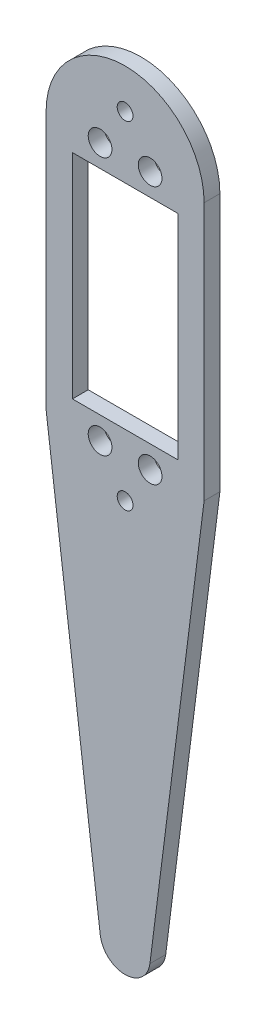
SolidWorks part; units mm, degrees
ref_plane "Front Plane" through (0, 0, 0) normal (0, 0, 1) x (1, 0, 0)
ref_plane "Top Plane" through (0, 0, 0) normal (0, 1, 0) x (1, 0, 0)
ref_plane "Right Plane" through (0, 0, 0) normal (1, 0, 0) x (0, 0, -1)
sketch "Sketch1" plane through (0, 0, 0) normal (0, 0, 1) x (1, 0, 0)
  line L0 (-5, -1011.6385) -> (-5, 48988.3615) construction
  line L1 (0, 0) -> (20, 0)
  line L2 (0, 0) -> (0, 40.5)
  line L3 (0, 40.5) -> (20, 40.5)
  line L4 (20, 0) -> (20, 40.5)
  line L5 (10, -959.5) -> (10, 49040.5) construction
  line L6 (5.25, -1016.8654) -> (5.25, -85.1896) construction
  line L7 (14.75, -1019.8958) -> (14.75, 48980.1042) construction
  line L8 (25, -978.4803) -> (25, 49021.5197) construction
  line L9 (-979.0853, 44.75) -> (49020.9147, 44.75) construction
  line L10 (-999.9631, -4.25) -> (49000.0369, -4.25) construction
  line L11 (-5, 44.75) -> (-5, -4.25)
  line L12 (25, 44.75) -> (25, -4.25)
  line L13 (-1010.4081, 30.36) -> (48989.5919, 30.36) construction
  line L14 (-990, -89.64) -> (49010, -89.64) construction
  line L15 (-5, -4.25) -> (5.2876, -85.4868)
  line L16 (25, -4.25) -> (14.7124, -85.4868)
  line L17 (5.25, -6.5) -> (5.25, 48983.1346) construction
  circle A0 centre (14.75, -4.25) radius 2.25
  circle A1 centre (5.25, -4.25) radius 2.25
  circle A2 centre (14.75, 44.75) radius 2.25
  circle A3 centre (5.25, 44.75) radius 2.25
  arc A4 (25, 44.75) -> (-5, 44.75) centre (10, 44.75) ccw
  arc A5 (5.2876, -85.4868) -> (14.7124, -85.4868) centre (10, -84.89) ccw
  circle A6 centre (10, 52.25) radius 1.5
  circle A7 centre (10, -11.75) radius 1.5
  point P10 (10, 40.5)
  dimension "D8" = 4.5
  dimension "D9" = 4.5
  dimension "D10" = 4.5
  dimension "D11" = 4.5
  dimension "D12" = 40.5
  dimension "D15" = 4.75
  dimension "D16" = 3
  dimension "D17" = 3
  dimension "D18" = 7.5
  dimension "D1" = 10
  dimension "D2" = 4.75
  dimension "D3" = 4.75
  dimension "D4" = 4.25
  dimension "D5" = 10.14
  dimension "D6" = 5
  dimension "D7" = 4.25
  dimension "D13" = 49
  dimension "D14" = 120
  dimension "D19" = 7.5
extrude "Boss-Extrude1" add sketch "Sketch1" along normal blind 3
